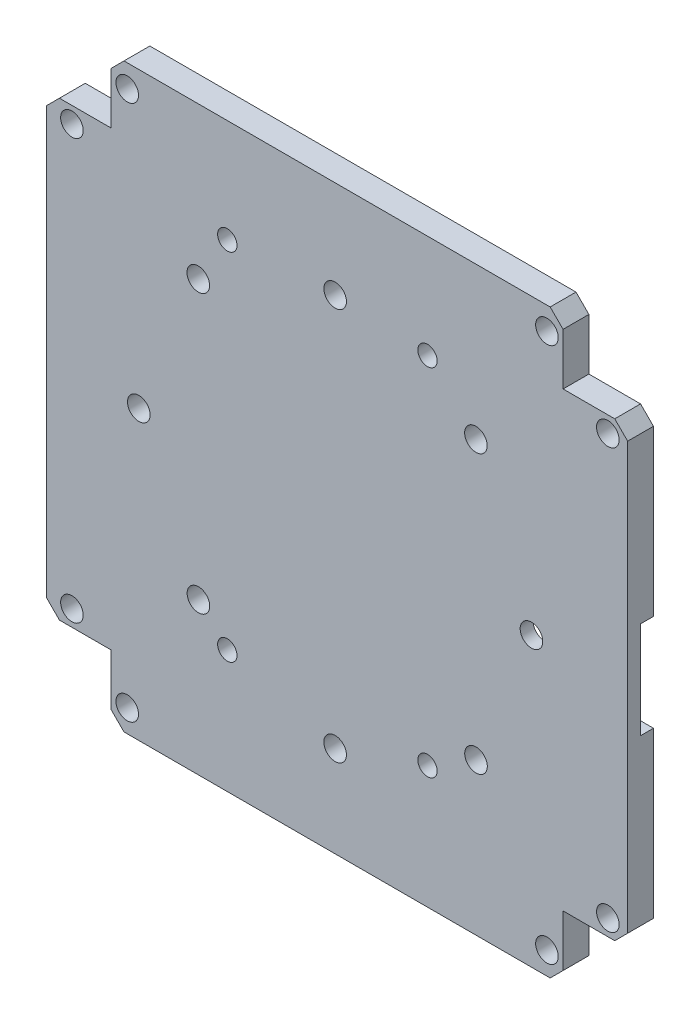
SolidWorks part; units mm, degrees
ref_plane "Plan de face" through (0, 0, 0) normal (0, 0, 1) x (1, 0, 0)
ref_plane "Plan de dessus" through (0, 0, 0) normal (0, 1, 0) x (1, 0, 0)
ref_plane "Plan de droite" through (0, 0, 0) normal (1, 0, 0) x (0, 0, -1)
sketch "Sketch1" plane through (0, 0, 0) normal (0, 0, 1) x (1, 0, 0)
  line L1 (-0.2317, 0.1934) -> (89.7683, 0.1934)
  line L2 (-0.2317, 0.1934) -> (-0.2317, 70.1934)
  line L3 (-0.2317, 70.1934) -> (89.7683, 70.1934)
  line L4 (89.7683, 0.1934) -> (89.7683, 70.1934)
  dimension "D1" = 70
  dimension "D2" = 90
extrude "Boss-Extrude1" add sketch "Sketch1" along normal blind 4
sketch "Sketch2" plane through (0, 0, 4) normal (0, 0, 1) x (1, 0, 0)
  line L0 (89.7683, 70.1934) -> (-0.2317, 70.1934) construction
  line L6 (-0.2317, 70.1934) -> (-0.2317, 0.1934) construction
  line L7 (89.7683, 0.1934) -> (89.7683, 70.1934) construction
  line L9 (-0.2317, 0.1934) -> (89.7683, 0.1934) construction
  circle A0 centre (3.7036, 2.6934) radius 1.75
  circle A1 centre (86.7036, 2.6944) radius 1.75
  circle A2 centre (86.7033, 67.6934) radius 1.75
  circle A3 centre (3.7033, 67.6934) radius 1.75
  circle A4 centre (23.2977, 13.6934) radius 1.75
  circle A5 centre (66.2841, 13.6934) radius 1.75
  circle A6 centre (66.2683, 56.6934) radius 1.75
  circle A7 centre (23.2683, 56.6934) radius 1.75
  dimension "D7" = 3.5
  dimension "D8" = 3.5
  dimension "D9" = 3.5
  dimension "D10" = 3.5
  dimension "D22" = 3.5
  dimension "D23" = 3.5
  dimension "D24" = 3.5
  dimension "D25" = 3.5
  dimension "D3" = 3.065
  dimension "D4" = 83
  dimension "D5" = 2.5
  dimension "D6" = 2.5
  dimension "D15" = 13.5
  dimension "D16" = 23.5295
  dimension "D17" = 13.5
  dimension "D18" = 13.5
  dimension "D19" = 23.5
  dimension "D20" = 13.5
  dimension "D21" = 23.5
extrude "Cut-Extrude1" cut sketch "Sketch2" against normal blind 5
chamfer "Chamfer1" distance 2 angle 45 1 edges at (89.7683, 0.1934, 2)
chamfer "Chamfer2" distance 2 angle 45 1 edges at (-0.2317, 0.1934, 2)
chamfer "Chamfer3" distance 2 angle 45 1 edges at (-0.2317, 70.1934, 2)
chamfer "Chamfer4" distance 2 angle 45 1 edges at (89.7683, 70.1934, 2)
sketch "Sketch4" plane through (0, 0.1934, 0) normal (0, -1, 0) x (-1, 0, 0)
  line L0 (-1.7683, 0) -> (-87.7683, 0) construction
  line L1 (-9.7683, -4) -> (-79.7683, -4)
  line L2 (-9.7683, -4) -> (-9.7683, 0)
  line L3 (-9.7683, 0) -> (-79.7683, 0)
  line L4 (-79.7683, -4) -> (-79.7683, 0)
  dimension "D1" = 70
  dimension "D2" = 8
  dimension "D3" = 4
  dimension "D4" = 0
sketch "Sketch5" plane through (0, 70.1934, 0) normal (0, 1, 0) x (1, 0, 0)
  line L0 (87.7683, 0) -> (1.7683, 0) construction
  line L1 (9.7683, -4) -> (79.7683, -4)
  line L2 (9.7683, -4) -> (9.7683, 0)
  line L3 (9.7683, 0) -> (79.7683, 0)
  line L4 (79.7683, -4) -> (79.7683, 0)
  dimension "D1" = 70
  dimension "D2" = 8
  dimension "D3" = 4
  dimension "D4" = 0
extrude "Boss-Extrude3" add sketch "Sketch5" along normal blind 10
extrude "Boss-Extrude4" add sketch "Sketch4" along normal blind 10
sketch "Sketch6" plane through (0, 0, 0) normal (0, 0, -1) x (-1, 0, 0)
  line L0 (-79.7683, 80.1934) -> (-79.7683, 70.1934) construction
  line L2 (-79.7683, -9.8066) -> (-79.7683, 0.1934) construction
  line L5 (-79.7683, 80.1934) -> (-9.7683, 80.1934) construction
  circle A0 centre (-12.2683, 76.6934) radius 1.75
  circle A1 centre (-77.2683, 76.6934) radius 1.75
  circle A2 centre (-77.2683, -6.3066) radius 1.75
  circle A3 centre (-12.2683, -6.3066) radius 1.75
  dimension "D7" = 3.5
  dimension "D8" = 3.5
  dimension "D9" = 3.5
  dimension "D10" = 3.5
  dimension "D1" = 83
  dimension "D2" = 83
  dimension "D3" = 65
  dimension "D4" = 65
  dimension "D5" = 2.5
  dimension "D6" = 2.5
  dimension "D11" = 3.5
  dimension "D12" = 3.5
extrude "Cut-Extrude2" cut sketch "Sketch6" against normal blind 10
chamfer "Chamfer5" distance 2 angle 45 4 edges at (9.7683, -9.8066, 2) (79.7683, -9.8066, 2) (9.7683, 80.1934, 2) (79.7683, 80.1934, 2)
sketch "Sketch7" plane through (0, 0, 0) normal (0, 0, -1) x (-1, 0, 0)
  line L0 (-24.7683, 55.1934) -> (-64.7683, 55.1934)
  line L1 (-64.7683, 55.1934) -> (-64.7683, 15.1934)
  line L2 (-64.7683, 15.1934) -> (-24.7683, 15.1934)
  line L3 (-24.7683, 15.1934) -> (-24.7683, 55.1934)
  line L4 (-77.7683, 80.1934) -> (-11.7683, 80.1934) construction
  line L5 (0.2317, 68.1934) -> (0.2317, 2.1934) construction
  dimension "D1" = 40
  dimension "D2" = 40
  dimension "D3" = 25
  dimension "D4" = 25
extrude "Cut-Extrude3" cut sketch "Sketch7" against normal blind 2
sketch "Sketch8" plane through (0, 0, 0) normal (0, 0, -1) x (-1, 0, 0)
  line L0 (-64.7683, 27.6934) -> (-89.7683, 27.6934)
  line L1 (-64.7683, 55.1934) -> (-64.7683, 15.1934) construction
  line L2 (-89.7683, 27.6934) -> (-89.7683, 42.6934)
  line L3 (-89.7683, 42.6934) -> (-64.7683, 42.6934)
  line L5 (-64.7683, 27.6934) -> (-64.7683, 42.6934)
  dimension "D1" = 15
  dimension "D2" = 25
  dimension "D3" = 12.5
extrude "Cut-Extrude4" cut sketch "Sketch8" against normal blind 2
sketch "Sketch9" plane through (0, 0, 0) normal (0, 0, -1) x (-1, 0, 0)
  line L0 (-24.7683, 55.1934) -> (-64.7683, 55.1934) construction
  circle A0 centre (-27.7683, 9.1934) radius 1.5
  circle A3 centre (-58.7683, 9.1934) radius 1.5
  circle A4 centre (-27.7683, 64.1934) radius 1.5
  circle A5 centre (-58.7683, 64.1934) radius 1.5
  dimension "D6" = 3
  dimension "D7" = 3
  dimension "D8" = 3
  dimension "D9" = 3
  dimension "D1" = 31
  dimension "D2" = 3
  dimension "D3" = 6
  dimension "D4" = 6
  dimension "D5" = 6
  dimension "D10" = 9
  dimension "D11" = 9
extrude "Cut-Extrude5" cut sketch "Sketch9" against normal blind 4
sketch "Sketch10" plane through (0, 0, 0) normal (0, 0, -1) x (-1, 0, 0)
  circle A9 centre (-74.8716, 34.731) radius 1.75
  circle A10 centre (-44.466, 4.3254) radius 1.75
  circle A11 centre (-14.0604, 34.731) radius 1.75
  circle A12 centre (-44.466, 65.1366) radius 1.75
  dimension "D2" = 43
  dimension "D1" = 43
  dimension "D3" = 3.5
  dimension "D4" = 3.5
  dimension "D5" = 3.5
  dimension "D6" = 3.5
extrude "Cut-Extrude6" cut sketch "Sketch10" against normal blind 10
